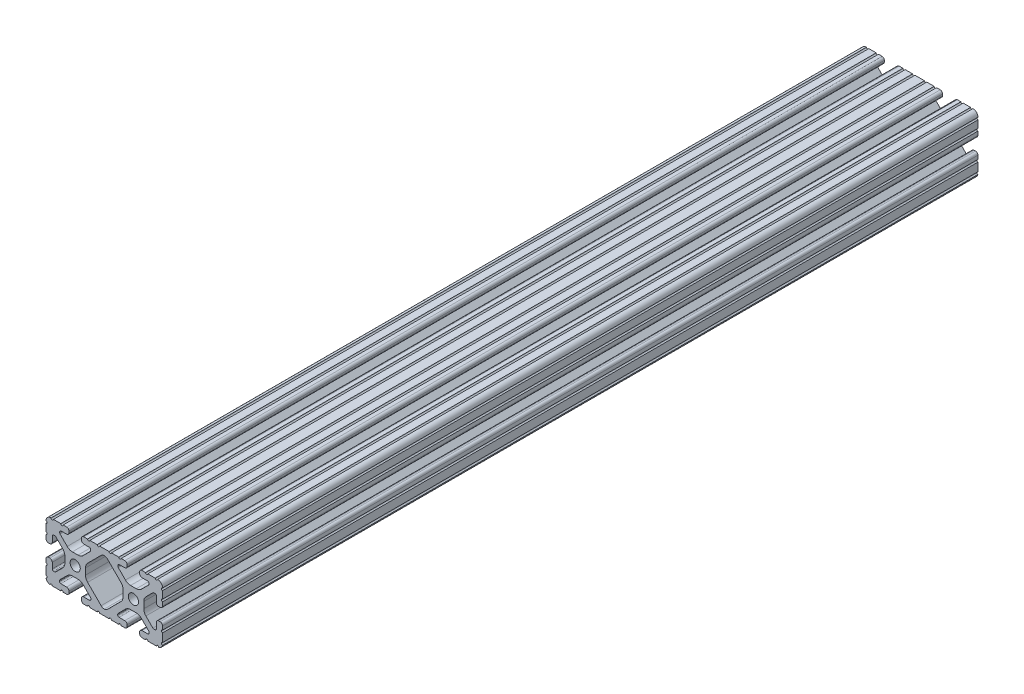
SolidWorks part; units mm, degrees
material "6061 Alloy"
ref_plane "Front Plane" through (0, 0, 0) normal (0, 0, 1) x (1, 0, 0)
ref_plane "Top Plane" through (0, 0, 0) normal (0, 1, 0) x (1, 0, 0)
ref_plane "Right Plane" through (0, 0, 0) normal (1, 0, 0) x (0, 0, -1)
sketch "Sketch1" plane through (0, 0, 0) normal (0, 0, 1) x (1, 0, 0)
  line L0 (-3.1211, -19.05) -> (3.1211, -19.05)
  line L1 (-38.1, 10.287) -> (-38.1, 14.3752)
  line L2 (0, -34.5561) -> (0, 32.8014) construction
  line L3 (-38.1, 0) -> (0, 0) construction
  line L4 (-38.1, 9.5497) -> (-38.1, 10.287)
  line L5 (-19.05, 19.05) -> (-19.05, -20.2827) construction
  line L6 (0, -15.1247) -> (0, -15.1131) construction
  line L7 (9.1761, 12.9058) -> (13.8525, 8.2294)
  line L8 (8.9158, 14.097) -> (8.9158, 13.5344)
  line L9 (13.4112, 14.986) -> (9.8048, 14.986)
  line L10 (14.986, 17.4968) -> (14.986, 16.5608)
  line L11 (10.9975, 19.05) -> (13.4328, 19.05)
  line L12 (8.6331, 19.05) -> (9.4735, 19.05)
  line L13 (4.6451, 19.05) -> (8.6331, 19.05)
  line L14 (31.792, 10.0266) -> (27.1976, 5.4321)
  line L15 (33.147, 10.287) -> (32.4207, 10.287)
  line L16 (29.2071, 19.05) -> (33.2963, 19.05)
  line L17 (28.4698, 19.05) -> (29.2071, 19.05)
  line L18 (-38.1, 5.6388) -> (-38.1, 8.0257)
  line L19 (24.5589, 19.05) -> (26.9458, 19.05)
  line L20 (23.114, 16.5608) -> (23.114, 17.4806)
  line L21 (28.2952, 14.986) -> (24.6888, 14.986)
  line L22 (29.1842, 13.5344) -> (29.1842, 14.097)
  line L23 (-34.036, 9.398) -> (-34.036, 5.6388)
  line L24 (-35.6108, 4.064) -> (-36.5252, 4.064)
  line L25 (24.2475, 8.2294) -> (28.9239, 12.9058)
  line L26 (25.8064, -2.0735) -> (25.8064, 2.0735)
  line L27 (35.6108, 4.064) -> (36.5252, 4.064)
  line L28 (34.036, 9.398) -> (34.036, 5.6388)
  line L29 (38.1, 5.6388) -> (38.1, 8.0257)
  line L30 (38.1, 9.5497) -> (38.1, 10.287)
  line L31 (38.1, 10.287) -> (38.1, 14.3752)
  line L32 (17.2111, 6.8382) -> (20.8889, 6.8382)
  line L33 (2.077, 14.2576) -> (10.9024, 5.4321)
  line L34 (-31.792, -10.0266) -> (-27.1976, -5.4321)
  line L35 (-33.147, -10.287) -> (-32.4207, -10.287)
  line L36 (-29.2071, -19.05) -> (-34.0473, -19.05)
  line L37 (-28.4698, -19.05) -> (-29.2071, -19.05)
  line L38 (-24.6888, -19.05) -> (-26.9458, -19.05)
  line L39 (12.2936, -2.0735) -> (12.2936, 2.0735)
  line L40 (-23.114, -16.5608) -> (-23.114, -17.4752)
  line L41 (-28.448, -14.986) -> (-24.6888, -14.986)
  line L42 (-29.337, -13.6872) -> (-29.337, -14.097)
  line L43 (2.077, -14.2576) -> (10.9024, -5.4321)
  line L44 (-3.1211, 19.05) -> (3.1211, 19.05)
  line L45 (8.763, -14.097) -> (8.763, -13.6872)
  line L46 (-24.2475, -8.2294) -> (-29.0766, -13.0586)
  line L47 (-35.6108, -4.064) -> (-36.5252, -4.064)
  line L48 (-34.036, -9.398) -> (-34.036, -5.6388)
  line L49 (-38.1, -5.6388) -> (-38.1, -8.0257)
  line L50 (-38.1, -9.5497) -> (-38.1, -10.287)
  line L51 (-38.1, -10.287) -> (-38.1, -15.036)
  line L52 (17.2111, -6.8382) -> (20.8889, -6.8382)
  line L53 (38.1, -10.287) -> (38.1, -15.036)
  line L54 (38.1, -9.5497) -> (38.1, -10.287)
  line L55 (38.1, -5.6388) -> (38.1, -8.0257)
  line L56 (34.036, -9.398) -> (34.036, -5.6388)
  line L57 (35.6108, -4.064) -> (36.5252, -4.064)
  line L58 (24.2475, -8.2294) -> (29.0766, -13.0586)
  line L59 (29.337, -13.6872) -> (29.337, -14.097)
  line L60 (-17.2111, -6.8382) -> (-20.8889, -6.8382)
  line L61 (-9.0234, -13.0586) -> (-13.8525, -8.2294)
  line L62 (-8.763, -14.097) -> (-8.763, -13.6872)
  line L63 (-13.4112, -14.986) -> (-9.652, -14.986)
  line L64 (-14.986, -17.4752) -> (-14.986, -16.5608)
  line L65 (-10.9975, -19.05) -> (-13.4112, -19.05)
  line L66 (28.448, -14.986) -> (24.6888, -14.986)
  line L67 (23.114, -16.5608) -> (23.114, -17.4752)
  line L68 (24.6888, -19.05) -> (26.9458, -19.05)
  line L69 (28.4698, -19.05) -> (29.2071, -19.05)
  line L70 (29.2071, -19.05) -> (34.0473, -19.05)
  line L71 (-8.6331, -19.05) -> (-9.4735, -19.05)
  line L72 (33.147, -10.287) -> (32.4207, -10.287)
  line L73 (31.792, -10.0266) -> (27.1976, -5.4321)
  line L74 (-4.6451, -19.05) -> (-8.6331, -19.05)
  line L75 (9.0234, -13.0586) -> (13.8525, -8.2294)
  line L76 (13.4112, -14.986) -> (9.652, -14.986)
  line L77 (-2.077, -14.2576) -> (-10.9024, -5.4321)
  line L78 (14.986, -17.4752) -> (14.986, -16.5608)
  line L79 (10.9975, -19.05) -> (13.4112, -19.05)
  line L80 (4.6451, -19.05) -> (8.6331, -19.05)
  line L81 (8.6331, -19.05) -> (9.4735, -19.05)
  line L83 (-12.2936, -2.0735) -> (-12.2936, 2.0735)
  line L84 (-25.8064, -2.0735) -> (-25.8064, 2.0735)
  line L85 (-2.077, 14.2576) -> (-10.9024, 5.4321)
  line L87 (-4.6451, 19.05) -> (-8.6331, 19.05)
  line L88 (-8.6331, 19.05) -> (-9.4735, 19.05)
  line L89 (-10.9975, 19.05) -> (-13.4328, 19.05)
  line L90 (-14.986, 17.4968) -> (-14.986, 16.5608)
  line L91 (-13.4112, 14.986) -> (-9.8048, 14.986)
  line L92 (-8.9158, 14.097) -> (-8.9158, 13.5344)
  line L93 (-9.1761, 12.9058) -> (-13.8525, 8.2294)
  line L94 (-17.2111, 6.8382) -> (-20.8889, 6.8382)
  line L95 (-24.2475, 8.2294) -> (-28.9239, 12.9058)
  line L96 (-29.1842, 13.5344) -> (-29.1842, 14.097)
  line L97 (-28.2952, 14.986) -> (-24.6888, 14.986)
  line L98 (-23.114, 16.5608) -> (-23.114, 17.4806)
  line L99 (-24.5589, 19.05) -> (-26.9458, 19.05)
  line L100 (-28.4698, 19.05) -> (-29.2071, 19.05)
  line L101 (-29.2071, 19.05) -> (-33.2963, 19.05)
  line L109 (-33.147, 10.287) -> (-32.4207, 10.287)
  line L165 (-31.792, 10.0266) -> (-27.1976, 5.4321)
  arc A0 (-38.1376, 15.8983) -> (-38.1, 14.3752) centre (-38.1, 15.1372) cw
  arc A1 (-38.1, 9.5497) -> (-38.1, 8.0257) centre (-38.1, 8.7877) cw
  arc A2 (9.1761, 12.9058) -> (8.9158, 13.5344) centre (9.8048, 13.5344) cw
  arc A3 (8.9158, 14.097) -> (9.8048, 14.986) centre (9.8048, 14.097) cw
  arc A4 (-36.5252, 4.064) -> (-38.1, 5.6388) centre (-36.5252, 5.6388) cw
  arc A5 (14.986, 16.5608) -> (13.4112, 14.986) centre (13.4112, 16.5608) cw
  arc A6 (13.4328, 19.05) -> (14.986, 17.4968) centre (13.4328, 17.4968) cw
  arc A7 (10.9975, 19.05) -> (9.4735, 19.05) centre (10.2355, 19.05) cw
  arc A8 (4.6451, 19.05) -> (3.1211, 19.05) centre (3.8831, 19.05) cw
  arc A9 (0, 15.1131) -> (2.077, 14.2576) centre (0.0116, 12.1921) cw
  arc A10 (25.8064, 2.0735) -> (27.1976, 5.4321) centre (30.5562, 2.0735) cw
  arc A11 (31.792, 10.0266) -> (32.4207, 10.287) centre (32.4207, 9.398) cw
  arc A12 (33.147, 10.287) -> (34.036, 9.398) centre (33.147, 9.398) cw
  arc A13 (34.8195, 19.0968) -> (38.1376, 15.8983) centre (34.903, 15.8631) cw
  arc A14 (34.8195, 19.0968) -> (33.2963, 19.05) centre (34.0579, 19.0734) cw
  arc A15 (28.4698, 19.05) -> (26.9458, 19.05) centre (27.7078, 19.05) cw
  arc A16 (23.114, 17.4806) -> (24.5589, 19.05) centre (24.6888, 17.4806) cw
  arc A17 (24.6888, 14.986) -> (23.114, 16.5608) centre (24.6888, 16.5608) cw
  arc A18 (28.2952, 14.986) -> (29.1842, 14.097) centre (28.2952, 14.097) cw
  arc A19 (29.1842, 13.5344) -> (28.9239, 12.9058) centre (28.2952, 13.5344) cw
  arc A20 (-35.5713, -19.05) -> (-38.1, -16.56) centre (-34.9455, -15.8855) cw
  arc A21 (34.036, 5.6388) -> (35.6108, 4.064) centre (35.6108, 5.6388) ccw
  arc A22 (36.5252, 4.064) -> (38.1, 5.6388) centre (36.5252, 5.6388) ccw
  arc A23 (38.1, 9.5497) -> (38.1, 8.0257) centre (38.1, 8.7877) ccw
  arc A24 (24.2475, 8.2294) -> (20.8889, 6.8382) centre (20.8889, 11.588) cw
  arc A25 (17.2111, 6.8382) -> (13.8525, 8.2294) centre (17.2111, 11.588) cw
  arc A26 (10.9024, 5.4321) -> (12.2936, 2.0735) centre (7.5438, 2.0735) cw
  arc A27 (0, -15.1131) -> (2.077, -14.2576) centre (0.0116, -12.1921) ccw
  arc A28 (-34.036, 5.6388) -> (-35.6108, 4.064) centre (-35.6108, 5.6388) cw
  arc A29 (-25.8064, -2.0735) -> (-27.1976, -5.4321) centre (-30.5562, -2.0735) cw
  arc A30 (-31.792, -10.0266) -> (-32.4207, -10.287) centre (-32.4207, -9.398) cw
  arc A31 (-33.147, -10.287) -> (-34.036, -9.398) centre (-33.147, -9.398) cw
  arc A33 (-35.5713, -19.05) -> (-34.0473, -19.05) centre (-34.8093, -19.05) cw
  arc A34 (-28.4698, -19.05) -> (-26.9458, -19.05) centre (-27.7078, -19.05) cw
  arc A35 (10.9024, -5.4321) -> (12.2936, -2.0735) centre (7.5438, -2.0735) ccw
  circle A36 centre (19.05, 0) radius 3.3274
  arc A37 (-23.114, -17.4752) -> (-24.6888, -19.05) centre (-24.6888, -17.4752) cw
  arc A38 (-24.6888, -14.986) -> (-23.114, -16.5608) centre (-24.6888, -16.5608) cw
  arc A39 (-28.448, -14.986) -> (-29.337, -14.097) centre (-28.448, -14.097) cw
  arc A40 (-29.337, -13.6872) -> (-29.0766, -13.0586) centre (-28.448, -13.6872) cw
  arc A41 (-24.2475, -8.2294) -> (-20.8889, -6.8382) centre (-20.8889, -11.588) cw
  arc A42 (-34.036, -5.6388) -> (-35.6108, -4.064) centre (-35.6108, -5.6388) ccw
  arc A43 (-36.5252, -4.064) -> (-38.1, -5.6388) centre (-36.5252, -5.6388) ccw
  arc A44 (-38.1, -9.5497) -> (-38.1, -8.0257) centre (-38.1, -8.7877) ccw
  arc A45 (-38.1, -16.56) -> (-38.1, -15.036) centre (-38.1, -15.798) ccw
  arc A46 (38.1, -16.56) -> (38.1, -15.036) centre (38.1, -15.798) cw
  arc A47 (38.1, -9.5497) -> (38.1, -8.0257) centre (38.1, -8.7877) cw
  arc A48 (36.5252, -4.064) -> (38.1, -5.6388) centre (36.5252, -5.6388) cw
  arc A49 (34.036, -5.6388) -> (35.6108, -4.064) centre (35.6108, -5.6388) cw
  arc A50 (24.2475, -8.2294) -> (20.8889, -6.8382) centre (20.8889, -11.588) ccw
  arc A51 (29.337, -13.6872) -> (29.0766, -13.0586) centre (28.448, -13.6872) ccw
  arc A52 (28.448, -14.986) -> (29.337, -14.097) centre (28.448, -14.097) ccw
  arc A53 (24.6888, -14.986) -> (23.114, -16.5608) centre (24.6888, -16.5608) ccw
  arc A54 (-17.2111, -6.8382) -> (-13.8525, -8.2294) centre (-17.2111, -11.588) cw
  arc A55 (-9.0234, -13.0586) -> (-8.763, -13.6872) centre (-9.652, -13.6872) cw
  arc A56 (-8.763, -14.097) -> (-9.652, -14.986) centre (-9.652, -14.097) cw
  arc A57 (-14.986, -16.5608) -> (-13.4112, -14.986) centre (-13.4112, -16.5608) cw
  arc A58 (-13.4112, -19.05) -> (-14.986, -17.4752) centre (-13.4112, -17.4752) cw
  arc A59 (-10.9975, -19.05) -> (-9.4735, -19.05) centre (-10.2355, -19.05) cw
  arc A60 (-4.6451, -19.05) -> (-3.1211, -19.05) centre (-3.8831, -19.05) cw
  arc A61 (23.114, -17.4752) -> (24.6888, -19.05) centre (24.6888, -17.4752) ccw
  arc A62 (28.4698, -19.05) -> (26.9458, -19.05) centre (27.7078, -19.05) ccw
  arc A63 (35.5713, -19.05) -> (34.0473, -19.05) centre (34.8093, -19.05) ccw
  arc A64 (35.5713, -19.05) -> (38.1, -16.56) centre (34.9379, -15.8778) ccw
  arc A65 (33.147, -10.287) -> (34.036, -9.398) centre (33.147, -9.398) ccw
  arc A66 (31.792, -10.0266) -> (32.4207, -10.287) centre (32.4207, -9.398) ccw
  arc A67 (-10.9024, -5.4321) -> (-12.2936, -2.0735) centre (-7.5438, -2.0735) cw
  arc A68 (0, -15.1131) -> (-2.077, -14.2576) centre (-0.0116, -12.1921) cw
  arc A69 (0, 15.1131) -> (-2.077, 14.2576) centre (-0.0116, 12.1921) ccw
  arc A70 (-10.9024, 5.4321) -> (-12.2936, 2.0735) centre (-7.5438, 2.0735) ccw
  arc A71 (25.8064, -2.0735) -> (27.1976, -5.4321) centre (30.5562, -2.0735) ccw
  arc A72 (9.0234, -13.0586) -> (8.763, -13.6872) centre (9.652, -13.6872) ccw
  arc A73 (8.763, -14.097) -> (9.652, -14.986) centre (9.652, -14.097) ccw
  arc A74 (17.2111, -6.8382) -> (13.8525, -8.2294) centre (17.2111, -11.588) ccw
  arc A75 (13.4112, -19.05) -> (14.986, -17.4752) centre (13.4112, -17.4752) ccw
  arc A76 (14.986, -16.5608) -> (13.4112, -14.986) centre (13.4112, -16.5608) ccw
  arc A77 (-4.6451, 19.05) -> (-3.1211, 19.05) centre (-3.8831, 19.05) ccw
  arc A78 (-10.9975, 19.05) -> (-9.4735, 19.05) centre (-10.2355, 19.05) ccw
  arc A79 (-13.4328, 19.05) -> (-14.986, 17.4968) centre (-13.4328, 17.4968) ccw
  arc A80 (-14.986, 16.5608) -> (-13.4112, 14.986) centre (-13.4112, 16.5608) ccw
  arc A81 (-8.9158, 14.097) -> (-9.8048, 14.986) centre (-9.8048, 14.097) ccw
  arc A82 (-9.1761, 12.9058) -> (-8.9158, 13.5344) centre (-9.8048, 13.5344) ccw
  arc A83 (-17.2111, 6.8382) -> (-13.8525, 8.2294) centre (-17.2111, 11.588) ccw
  arc A84 (-24.2475, 8.2294) -> (-20.8889, 6.8382) centre (-20.8889, 11.588) ccw
  arc A85 (-29.1842, 13.5344) -> (-28.9239, 12.9058) centre (-28.2952, 13.5344) ccw
  arc A86 (-28.2952, 14.986) -> (-29.1842, 14.097) centre (-28.2952, 14.097) ccw
  arc A87 (-24.6888, 14.986) -> (-23.114, 16.5608) centre (-24.6888, 16.5608) ccw
  arc A88 (-23.114, 17.4806) -> (-24.5589, 19.05) centre (-24.6888, 17.4806) ccw
  arc A89 (-28.4698, 19.05) -> (-26.9458, 19.05) centre (-27.7078, 19.05) ccw
  arc A90 (-34.8195, 19.0968) -> (-33.2963, 19.05) centre (-34.0579, 19.0734) ccw
  arc A91 (-34.8195, 19.0968) -> (-38.1376, 15.8983) centre (-34.903, 15.8631) ccw
  arc A92 (4.6451, -19.05) -> (3.1211, -19.05) centre (3.8831, -19.05) ccw
  arc A93 (10.9975, -19.05) -> (9.4735, -19.05) centre (10.2355, -19.05) ccw
  arc A94 (38.1376, 15.8983) -> (38.1, 14.3752) centre (38.1, 15.1372) ccw
  arc A96 (-33.147, 10.287) -> (-34.036, 9.398) centre (-33.147, 9.398) ccw
  arc A97 (-31.792, 10.0266) -> (-32.4207, 10.287) centre (-32.4207, 9.398) ccw
  arc A98 (-25.8064, 2.0735) -> (-27.1976, 5.4321) centre (-30.5562, 2.0735) ccw
  circle A101 centre (-19.05, 0) radius 3.3274
  point P34 (0, 19.05)
  point P79 (25.6765, 0)
  point P274 (0, -19.05)
  point P282 (-25.6765, 0)
  point P283 (-12.2936, 0)
  dimension "D1" = 38.1
  dimension "D4" = 6.6548
  dimension "D10" = 4.064
  dimension "D2" = 76.2
  dimension "D3" = 38.1
  dimension "D5" = 8.128
  dimension "D6" = 20.574
  dimension "D7" = 12.2936
  dimension "D8" = 4.064
  dimension "D9" = 4.064
extrude "Extrude1" add sketch "Sketch1" against normal blind 533.4
